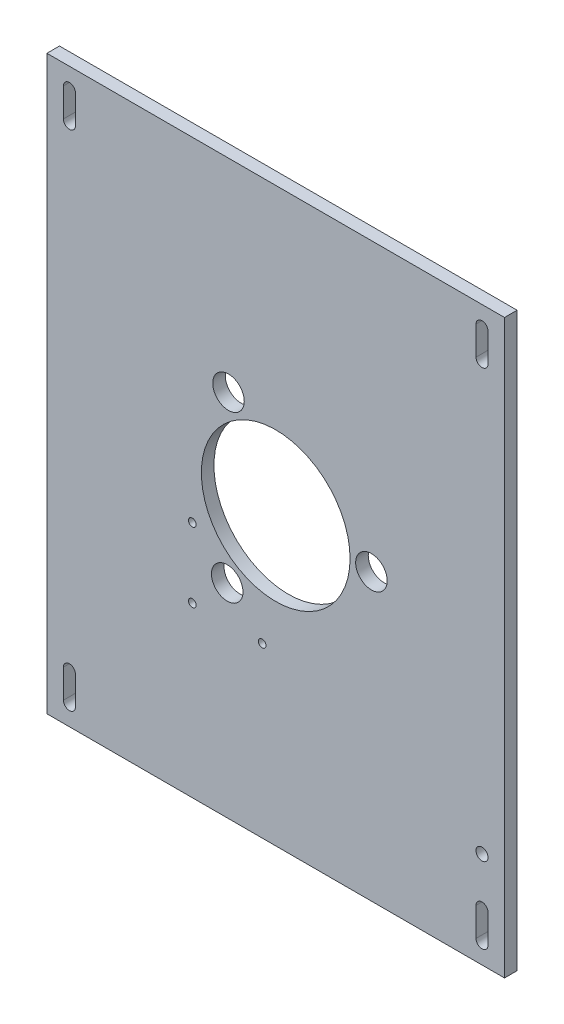
SolidWorks part; units mm, degrees
ref_plane "Front Plane" through (0, 0, 0) normal (0, 0, 1) x (1, 0, 0)
ref_plane "Top Plane" through (0, 0, 0) normal (0, 1, 0) x (1, 0, 0)
ref_plane "Right Plane" through (0, 0, 0) normal (1, 0, 0) x (0, 0, -1)
sketch "Sketch1" plane through (0, 0, 0) normal (0, 0, 1) x (1, 0, 0)
  line L1 (-101.6, -127) -> (101.6, -127)
  line L2 (-101.6, -127) -> (-101.6, 127)
  line L3 (-101.6, 127) -> (101.6, 127)
  line L4 (101.6, -127) -> (101.6, 127)
  line L5 (-101.6, -127) -> (101.6, 127) construction
  line L6 (-101.6, 127) -> (101.6, -127) construction
  circle A0 centre (0, 0) radius 33.02
  point P0 (0, 0)
  dimension "D3" = 66.04
  dimension "D1" = 203.2
  dimension "D2" = 254
extrude "Boss-Extrude1" add sketch "Sketch1" along normal blind 5.588
extrude "Cut-Extrude6" cut sketch "Sketch7" against normal blind 10
sketch "Sketch7" plane through (-207.786, -42.9964, 5.588) normal (0, 0, 1) x (0.9999, -0.012, 0)
  circle A0 centre (207.2559, 45.4831) radius 50 construction
  circle A1 centre (249.7555, 45.6619) radius 7
  circle A2 centre (249.7555, 45.6619) radius 7.5 construction
  dimension "D1" = 14
  dimension "D2" = 100
  dimension "D3" = 15
pattern_circular "CirPattern2" count 3 over 360 about axis through (0, 0, 0) along (0, 0, 1) of "Cut-Extrude6"
sketch "Sketch9" plane through (0, 0, 0) normal (0, 0, -1) x (-1, 0, 0)
  line L1 (6.0355, -52.1397) -> (37.0355, -52.1397) construction
  line L2 (6.0355, -52.1397) -> (6.0355, -21.1397) construction
  line L3 (6.0355, -21.1397) -> (37.0355, -21.1397) construction
  line L4 (37.0355, -52.1397) -> (37.0355, -21.1397) construction
  line L5 (6.0355, -52.1397) -> (37.0355, -21.1397) construction
  line L6 (6.0355, -21.1397) -> (37.0355, -52.1397) construction
  circle A0 centre (37.0355, -21.1397) radius 1.7
  circle A1 centre (37.0355, -52.1397) radius 1.7
  circle A2 centre (6.0355, -52.1397) radius 1.7
  point P0 (21.5355, -36.6397)
  dimension "D3" = 3.4
  dimension "D1" = 31
  dimension "D2" = 31
extrude "Cut-Extrude8" cut sketch "Sketch9" against normal through all
extrude "Cut-Extrude9" cut sketch "Sketch10" against normal through all
sketch "Sketch10" plane through (-338.2608, -104.8206, 5.588) normal (0, 0, 1) x (0.9999, -0.0127, 0)
  circle A1 centre (429.5653, 25.9633) radius 2.665
sketch "Sketch11" plane through (0, 0, 0) normal (0, 0, -1) x (-1, 0, 0)
  line L0 (-91.6, -86.99) -> (-91.6, -79.1401) construction
  line L1 (-91.6, -118.11) -> (-91.6, -105.41) construction
  line L2 (-94.265, -118.11) -> (-94.265, -105.41)
  line L3 (-88.935, -118.11) -> (-88.935, -105.41)
  line L4 (101.6, -127) -> (-101.6, -127) construction
  circle A0 centre (-91.6, -84.325) radius 2.665 construction
  arc A1 (-94.265, -118.11) -> (-88.935, -118.11) centre (-91.6, -118.11) ccw
  arc A2 (-88.935, -105.41) -> (-94.265, -105.41) centre (-91.6, -105.41) ccw
  point P7 (-91.6, -111.76)
  point P12 (-91.6, -91.2541)
  point P13 (-91.6, -84.4354)
  dimension "D1" = 12.7
  dimension "D2" = 8.89
extrude "Cut-Extrude10" cut sketch "Sketch11" against normal through all
mirror "Mirror1" about plane through (0, 0, 0) normal (1, 0, 0) of "Cut-Extrude10" second plane through (0, 0, 0) second plane normal (0, 1, 0)
